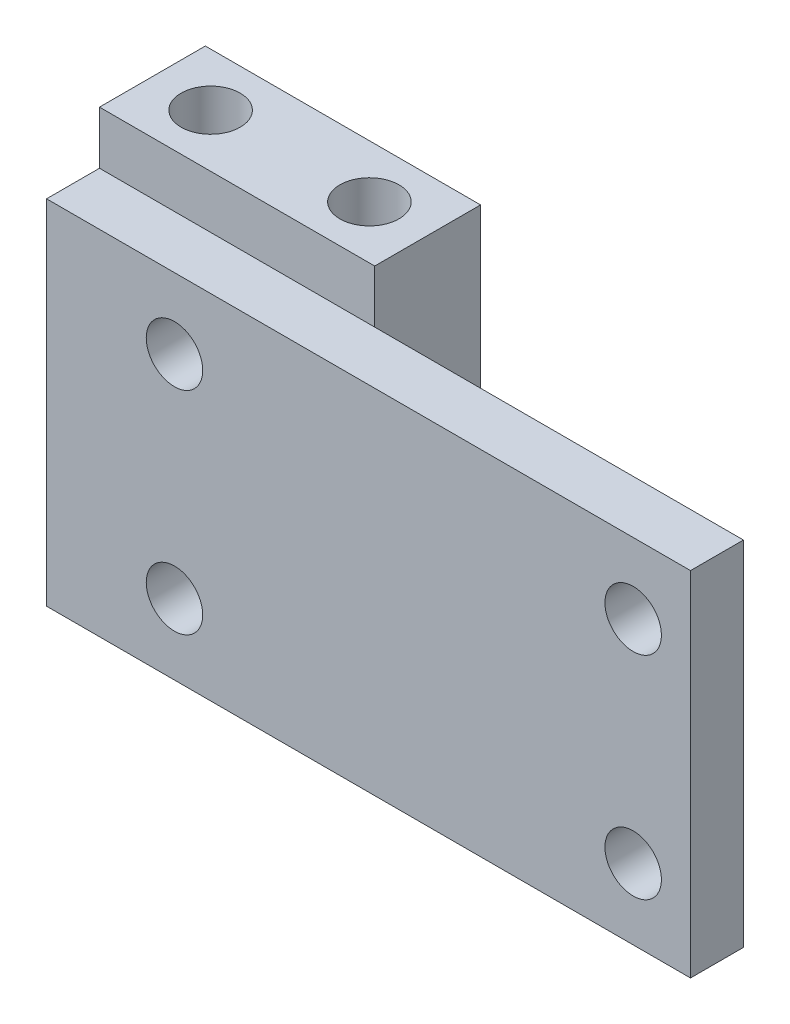
SolidWorks part; units mm, degrees
ref_plane "Front Plane" through (0, 0, 0) normal (0, 0, 1) x (1, 0, 0)
ref_plane "Top Plane" through (0, 0, 0) normal (0, 1, 0) x (1, 0, 0)
ref_plane "Right Plane" through (0, 0, 0) normal (1, 0, 0) x (0, 0, -1)
sketch "Sketch1" plane through (0, 0, 0) normal (0, 0, 1) x (1, 0, 0)
  line L1 (0, 0) -> (15.6, 0)
  line L2 (0, 0) -> (0, 26)
  line L3 (0, 26) -> (15.6, 26)
  line L4 (15.6, 0) -> (15.6, 26)
  dimension "D1" = 26
  dimension "D2" = 15.6
extrude "Boss-Extrude1" add sketch "Sketch1" along normal blind 6
sketch "Sketch2" plane through (0, 26, 0) normal (0, 1, 0) x (1, 0, 0)
  line L0 (0, -3) -> (15.6, -3) construction
  line L1 (0, -6) -> (0, 0) construction
  line L2 (15.6, -6) -> (15.6, 0) construction
  circle A0 centre (3.3, -3) radius 1.675
  circle A1 centre (12.3, -3) radius 1.675
  dimension "D3" = 3.35
  dimension "D1" = 3.3
  dimension "D2" = 3.3
extrude "Cut-Extrude1" cut sketch "Sketch2" against normal blind 4.5
sketch "Sketch3" plane through (0, 0, 0) normal (0, -1, 0) x (1, 0, 0)
  circle A1 centre (12.3, 3) radius 1.675
  circle A2 centre (12.3, 3) radius 1.675
  circle A3 centre (3.3, 3) radius 1.675
  circle A4 centre (3.3, 3) radius 1.675
  dimension "D1" = 0
  dimension "D2" = 0
extrude "Cut-Extrude2" cut sketch "Sketch3" against normal blind 4.5
sketch "Sketch4" plane through (0, 0, 6) normal (0, 0, 1) x (1, 0, 0)
  line L0 (0, 26) -> (0, 0) construction
  line L1 (0, 3) -> (36.5, 3)
  line L2 (0, 3) -> (0, 23)
  line L3 (0, 23) -> (36.5, 23)
  line L4 (36.5, 3) -> (36.5, 23)
  line L5 (0, 13) -> (36.5, 13) construction
  point P8 (0, 0)
  point P9 (0, 0)
  point P10 (0, 0)
  point P11 (0, 3)
  dimension "D1" = 20
  dimension "D2" = 36.5
extrude "Boss-Extrude2" add sketch "Sketch4" along normal blind 3
hole_wizard "CBORE for M3 SHCS4" positions "Sketch6" profile "Sketch7" counterbore size "M3" standard "ANSI Metric" end condition through all
sketch "Sketch6" plane through (0, 0, 0) normal (0, 0, -1) x (-1, 0, 0)
  line L0 (-36.5, 13) -> (0, 13) construction
  line L1 (-36.5, 3) -> (-36.5, 23) construction
  line L2 (0, 26) -> (0, 0) construction
  line L3 (-20.25, 13) -> (-20.25, 23) construction
  line L4 (-36.5, 23) -> (-15.6, 23) construction
  point P9 (-7.25, 19)
  point P21 (-7.25, 7)
  point P22 (0, 0)
  point P23 (-33.25, 7)
  point P24 (-33.25, 19)
  point P25 (0, 0)
  point P26 (-19.8809, 13)
  point P27 (-18.25, 13)
  dimension "D1" = 6
  dimension "D2" = 13
  dimension "D3" = 2
sketch "Sketch7" plane through (33.25, 19, 0) normal (1, 0, 0) x (0, 1, 0)
  line L0 (0, 0) -> (0, 9)
  line L1 (0, 9) -> (1.6, 9)
  line L3 (1.6, 9) -> (1.6, 3)
  line L4 (1.6, 3) -> (3.3, 3)
  line L5 (3.3, 3) -> (3.3, 0)
  line L7 (3.3, 0) -> (0, 0)
  line L11 (0, -6.35) -> (0, 107.95) construction
  dimension "Thru Hole Dia." = 3.2
  dimension "Thru Hole Depth" = 9
  dimension "C'Bore Dia." = 6.6
  dimension "C'Bore Depth" = 3
